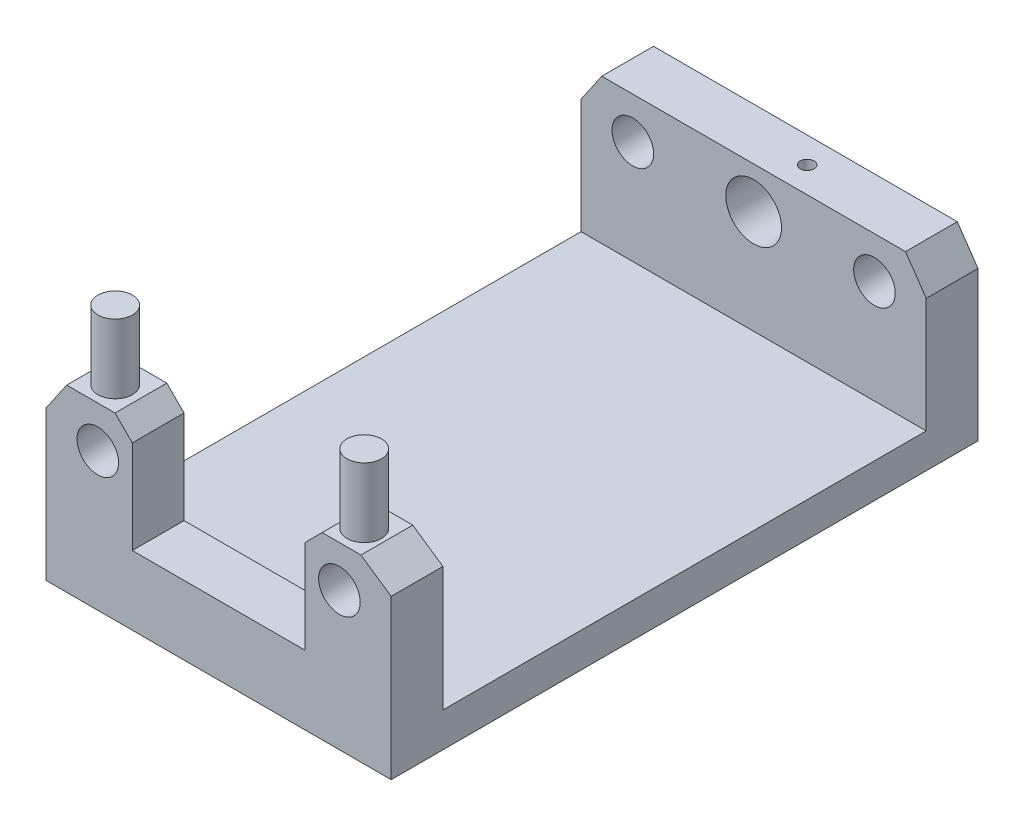
SolidWorks part; units mm, degrees
ref_plane "Front Plane" through (0, 0, 0) normal (0, 0, 1) x (1, 0, 0)
ref_plane "Top Plane" through (0, 0, 0) normal (0, 1, 0) x (1, 0, 0)
ref_plane "Right Plane" through (0, 0, 0) normal (1, 0, 0) x (0, 0, -1)
ref_plane "Plane1" through (0, 0, 85) normal (0, 0, 1) x (1, 0, 0)
sketch "Sketch1" plane through (0, 0, 85) normal (0, 0, 1) x (1, 0, 0)
  line L0 (50, -40) -> (50, 12)
  line L1 (50, 12) -> (-50, 12)
  line L2 (-50, 12) -> (-50, -40)
  line L3 (-50, -40) -> (50, -40)
extrude "Boss-Extrude1" add sketch "Sketch1" against normal blind 15
sketch "Sketch2" plane through (0, 0, 70) normal (0, 0, -1) x (-1, 0, 0)
  circle A0 centre (35, 0) radius 6
extrude "Boss-Extrude2" add sketch "Sketch2" along normal blind 140
ref_plane "Plane2" through (0, 0, -70) normal (0, 0, 1) x (1, 0, 0)
sketch "Sketch3" plane through (0, 0, -70) normal (0, 0, 1) x (1, 0, 0)
  line L0 (-50, 6) -> (-50, -40)
  line L1 (-50, -40) -> (50, -40)
  line L2 (50, -40) -> (50, 6)
  line L3 (50, 6) -> (-50, 6)
extrude "Boss-Extrude3" add sketch "Sketch3" against normal blind 15
sketch "Sketch4" plane through (0, 6, 0) normal (0, 1, 0) x (-1, 0, 0)
  line L0 (-50, -70) -> (50, -70)
  line L1 (50, -70) -> (50, -85)
  line L2 (50, -85) -> (-50, -85)
  line L3 (-50, -85) -> (-50, -70)
extrude "Boss-Extrude4" add sketch "Sketch4" along normal blind 6
sketch "Sketch5" plane through (0, 0, 70) normal (0, 0, -1) x (-1, 0, 0)
  line L0 (50, -40) -> (-50, -40)
  line L1 (-50, -40) -> (-50, -30)
  line L2 (-50, -30) -> (50, -30)
  line L3 (50, -30) -> (50, -40)
extrude "Boss-Extrude5" add sketch "Sketch5" along normal blind 30
sketch "Sketch6" plane through (0, 0, -70) normal (0, 0, 1) x (1, 0, 0)
  line L0 (50, -40) -> (-50, -40)
  line L1 (-50, -40) -> (-50, -30)
  line L2 (-50, -30) -> (50, -30)
  line L3 (50, -30) -> (50, -40)
extrude "Boss-Extrude6" add sketch "Sketch6" along normal blind 30
sketch "Sketch7" plane through (0, 0, 70) normal (0, 0, -1) x (-1, 0, 0)
  line L0 (25, 12) -> (-25, 12)
  line L1 (-25, 12) -> (-25, -20)
  line L2 (-25, -20) -> (25, -20)
  line L3 (25, -20) -> (25, 12)
extrude "Cut-Extrude1" cut sketch "Sketch7" against normal through all
sketch "Sketch8" plane through (0, 0, 0) normal (0, 1, 0) x (1, 0, 0)
  line L0 (41, 86) -> (35, 86)
  line L1 (35, 86) -> (35, 85)
  line L2 (35, 85) -> (41, 85)
  line L3 (41, 85) -> (41, 86)
  line L4 (35, 86) -> (35, 85) construction
revolve "Revolve1" add sketch "Sketch8" angle 360 about L4
sketch "Sketch9" plane through (0, 0, 0) normal (0, 1, 0) x (1, 0, 0)
  line L0 (-29, 86) -> (-35, 86)
  line L1 (-35, 86) -> (-35, 85)
  line L2 (-35, 85) -> (-29, 85)
  line L3 (-29, 85) -> (-29, 86)
  line L4 (-35, 86) -> (-35, 85) construction
revolve "Revolve2" add sketch "Sketch9" angle 360 about L4
sketch "Sketch10" plane through (0, 0, 0) normal (0, 1, 0) x (1, 0, 0)
  line L0 (41, -85) -> (35, -85)
  line L1 (35, -85) -> (35, -86)
  line L2 (35, -86) -> (41, -86)
  line L3 (41, -86) -> (41, -85)
  line L4 (35, -85) -> (35, -86) construction
revolve "Revolve3" add sketch "Sketch10" angle 360 about L4
sketch "Sketch11" plane through (0, 0, 0) normal (0, 1, 0) x (1, 0, 0)
  line L0 (-29, -85) -> (-35, -85)
  line L1 (-35, -85) -> (-35, -86)
  line L2 (-35, -86) -> (-29, -86)
  line L3 (-29, -86) -> (-29, -85)
  line L4 (-35, -85) -> (-35, -86) construction
revolve "Revolve4" add sketch "Sketch11" angle 360 about L4
sketch "Sketch12" plane through (0, 0, 0) normal (0, 1, 0) x (1, 0, 0)
  line L0 (41, 70) -> (35, 70)
  line L1 (35, 70) -> (35, -70)
  line L2 (35, -70) -> (41, -70)
  line L3 (41, -70) -> (41, 70)
  line L4 (35, 70) -> (35, -70) construction
revolve "Revolve5" add sketch "Sketch12" angle 360 about L4
hole_wizard "Ø10.0 (10) Diameter Hole1" positions "Sketch14" profile "Sketch13" hole size "Ø10.0" standard "ANSI Metric"
sketch "Sketch14" plane through (0, -40, 0) normal (0, -1, 0) x (-1, 0, 0)
  point P0 (35, -55)
  point P1 (-35, -55)
  point P2 (-35, 54.9982)
  point P3 (35, 54.9982)
sketch "Sketch13" plane through (-35, -40, 55) normal (1, 0, 0) x (0, 0, -1)
  line L0 (0, 0) -> (0, 10)
  line L1 (0, 10) -> (5, 10)
  line L2 (5, 10) -> (5, 0)
  line L5 (5, 0) -> (0, 0)
  line L11 (0, -6.35) -> (0, 107.95) construction
  dimension "Thru Hole Dia." = 10
  dimension "Thru Hole Depth" = 10
hole_wizard "Ø4.0 (4) Diameter Hole1" positions "Sketch16" profile "Sketch15" hole size "Ø4.0" standard "ANSI Metric"
sketch "Sketch16" plane through (0, 12, 0) normal (0, 1, 0) x (1, 0, 0)
  point P0 (8, 77.5)
sketch "Sketch15" plane through (8, 12, -77.5) normal (1, 0, 0) x (0, 0, 1)
  line L0 (0, 0) -> (0, 20)
  line L1 (0, 20) -> (2, 20)
  line L2 (2, 20) -> (2, 0)
  line L5 (2, 0) -> (0, 0)
  line L10 (0, 20) -> (-2, 20) construction
  line L11 (0, -6.35) -> (0, 107.95) construction
  dimension "Hole Dia." = 4
  dimension "Hole Depth" = 20
  dimension "Drill Angle" = 180
hole_wizard "Ø16.0 (16) Diameter Hole1" positions "Sketch18" profile "Sketch17" hole size "Ø16.0" standard "ANSI Metric"
sketch "Sketch18" plane through (0, 0, -70) normal (0, 0, 1) x (1, 0, 0)
  point P0 (0, 0)
sketch "Sketch17" plane through (0, 0, -70) normal (1, 0, 0) x (0, -1, 0)
  line L0 (0, 0) -> (0, 16)
  line L1 (0, 16) -> (8, 16)
  line L2 (8, 16) -> (8, 0)
  line L5 (8, 0) -> (0, 0)
  line L11 (0, -6.35) -> (0, 107.95) construction
  dimension "Thru Hole Dia." = 16
  dimension "Thru Hole Depth" = 16
chamfer "Chamfer1" distance 8.75 angle 34.439 4 edges at (50, 12, -77.5) (-50, 12, 77.5) (-50, 12, -77.5) (50, 12, 77.5)
chamfer "Chamfer2" distance 5 angle 45 2 edges at (25, 12, 77.5) (-25, 12, 77.5)
sketch "Sketch19" plane through (0, 0, -86) normal (0, 0, -1) x (-1, 0, 0)
  circle A0 centre (-35, 0) radius 6
  circle A1 centre (35, 0) radius 6
extrude "Cut-Extrude2" cut sketch "Sketch19" against normal blind 300
sketch "Sketch20" plane through (-50, 0, 0) normal (-1, 0, 0) x (0, 0, 1)
  line L0 (-40, -40) -> (40, -40)
  line L1 (40, -40) -> (40, -30)
  line L2 (40, -30) -> (-40, -30)
  line L3 (-40, -30) -> (-40, -40)
extrude "Boss-Extrude7" add sketch "Sketch20" against normal blind 100
sketch "Sketch21" plane through (0, -30, 0) normal (0, 1, 0) x (1, 0, 0)
  circle A0 centre (-35, 54.9982) radius 5
  circle A1 centre (35, 54.9982) radius 5
  circle A3 centre (35, -55) radius 5
  circle A4 centre (-35, -55) radius 5
extrude "Boss-Extrude8" add sketch "Sketch21" against normal blind 10
sketch "Sketch22" plane through (0, 0, 85) normal (0, 0, 1) x (1, 0, 0)
  circle A0 centre (-50, 0) radius 7.5
  circle A2 centre (50, 0) radius 7.5
  dimension "D1" = 15
sketch "Sketch23" plane through (0, 12, 0) normal (0, 1, 0) x (1, 0, 0)
  line L0 (0, 0) -> (0, 31.6089)
  circle A1 centre (-37.0744, -77.8906) radius 5
  circle A2 centre (35.0832, -77.8906) radius 5
  dimension "D1" = 10
  dimension "D2" = 10
extrude "Boss-Extrude10" add sketch "Sketch23" along normal blind 20 contours A1 | A2
sketch "Sketch24" plane through (0, 0, -85) normal (0, 0, -1) x (-1, 0, 0)
  circle A0 centre (0, 0) radius 8.075
  dimension "D1" = 16.15
extrude "Cut-Extrude3" cut sketch "Sketch24" against normal blind 40
sketch "Sketch25" plane through (0, 0, 85) normal (0, 0, 1) x (1, 0, 0)
  circle A0 centre (-35, 0) radius 6.025
  circle A1 centre (35, 0) radius 6.025
  dimension "D1" = 12.05
  dimension "D2" = 12.05
extrude "Cut-Extrude4" cut sketch "Sketch25" against normal blind 187
